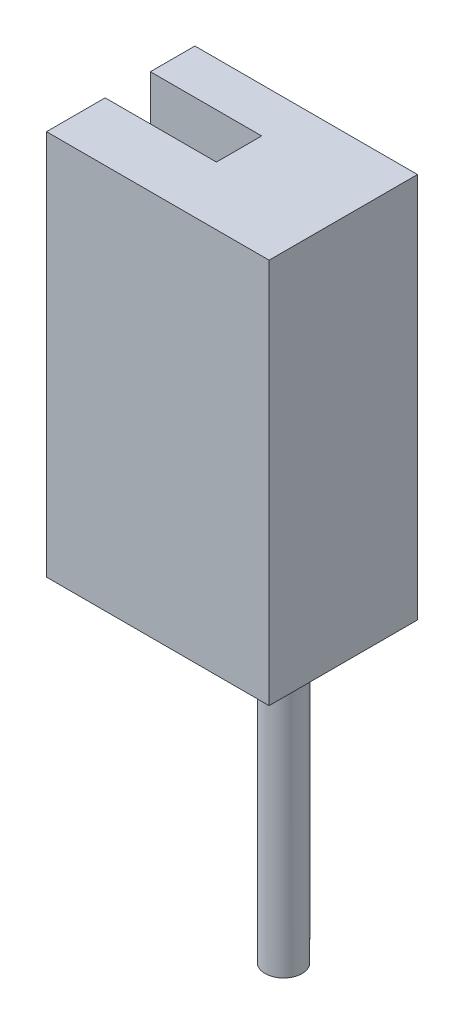
SolidWorks part; units mm, degrees
ref_plane "Front Plane" through (0, 0, 0) normal (0, 0, 1) x (1, 0, 0)
ref_plane "Top Plane" through (0, 0, 0) normal (0, 1, 0) x (1, 0, 0)
ref_plane "Right Plane" through (0, 0, 0) normal (1, 0, 0) x (0, 0, -1)
sketch "Sketch1" plane through (0, 0, 0) normal (0, 0, 1) x (1, 0, 0)
  line L1 (40.514, 0) -> (10.514, 0)
  line L2 (40.514, 0) -> (40.514, -52)
  line L3 (40.514, -52) -> (10.514, -52)
  line L4 (10.514, 0) -> (10.514, -52)
  dimension "D1" = 30
  dimension "D2" = 52
sketch "Sketch2" plane through (0, 0, 0) normal (0, 0, 1) x (1, 0, 0)
extrude "Boss-Extrude1" add sketch "Sketch1" along normal blind 20
sketch "Sketch3" plane through (0, 0, 0) normal (0, 1, 0) x (1, 0, 0)
  line L0 (10.514, -20) -> (10.514, 0) construction
  line L1 (10.514, -6) -> (25.514, -6)
  line L2 (10.514, -6) -> (10.514, -12.1)
  line L3 (10.514, -12.1) -> (25.514, -12.1)
  line L4 (25.514, -6) -> (25.514, -12.1)
  dimension "D1" = 15
  dimension "D2" = 6.1
  dimension "D3" = 6
extrude "Cut-Extrude1" cut sketch "Sketch3" against normal through all
sketch "Sketch4" plane through (0, -52, 0) normal (0, -1, 0) x (-1, 0, 0)
  line L0 (-25.514, -12.1) -> (-25.514, -6) construction
  circle A0 centre (-31.514, -9.05) radius 2.5
  dimension "D2" = 5
  dimension "D1" = 6
extrude "Boss-Extrude2" add sketch "Sketch4" along normal blind 40
